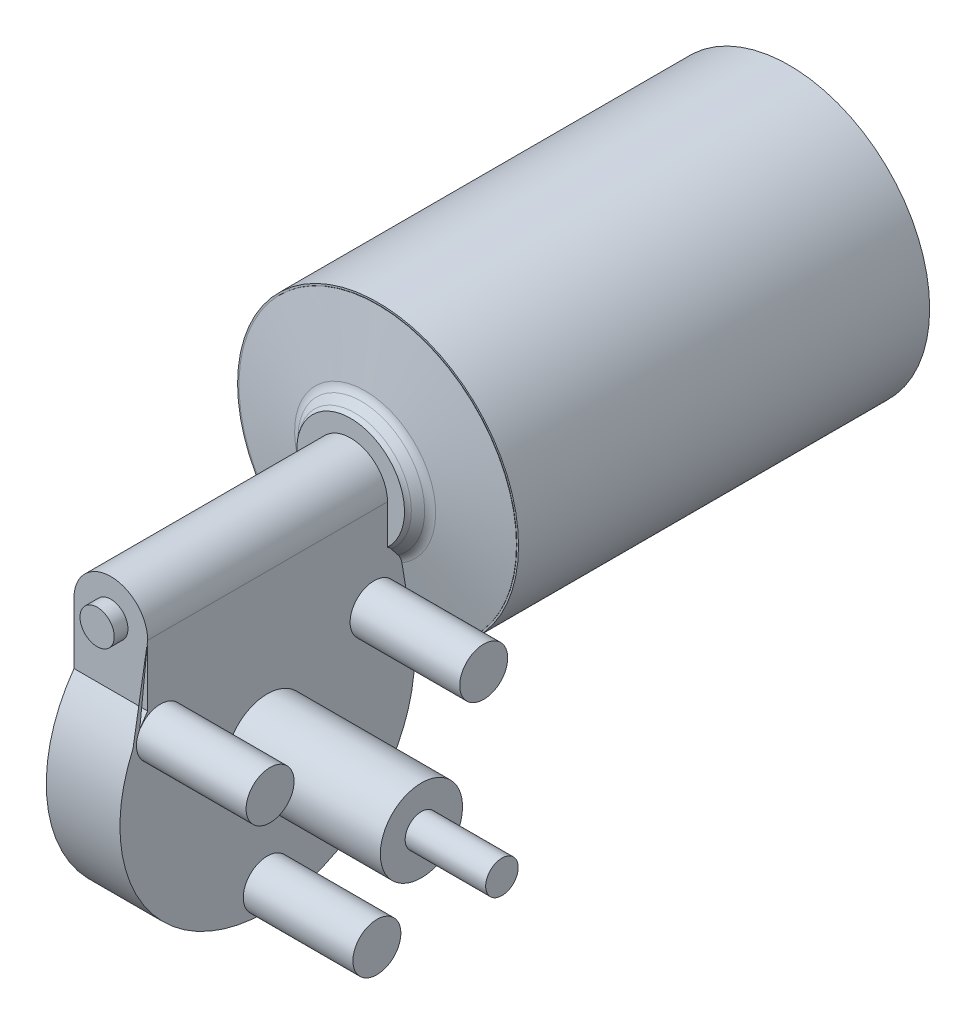
SolidWorks part; units mm, degrees
ref_plane "Front Plane" through (0, 0, 0) normal (0, 0, 1) x (1, 0, 0)
ref_plane "Top Plane" through (0, 0, 0) normal (0, 1, 0) x (1, 0, 0)
ref_plane "Right Plane" through (0, 0, 0) normal (1, 0, 0) x (0, 0, -1)
sketch "Sketch1" plane through (0, 0, 0) normal (0, 0, 1) x (1, 0, 0)
  circle A0 centre (0, 0) radius 41
  dimension "D1" = 82
extrude "Boss-Extrude1" add sketch "Sketch1" along normal mid plane 124
sketch "Sketch2" plane through (0, 0, 62) normal (0, 0, 1) x (1, 0, 0)
  circle A0 centre (0, 0) radius 41
extrude "Boss-Extrude2" add sketch "Sketch2" along normal mid plane 8
sketch "Sketch3" plane through (0, 0, 66) normal (0, 0, 1) x (1, 0, 0)
  circle A0 centre (0, 0) radius 40.5
  circle A1 centre (0, 0) radius 41 construction
  circle A2 centre (0, 0) radius 41
  dimension "D1" = 0.5
extrude "Cut-Extrude1" cut sketch "Sketch3" against normal blind 8
sketch "Sketch4" plane through (0, 0, 0) normal (1, 0, 0) x (0, 0, -1)
  line L0 (-58, 41) -> (-61.774, 20.5889)
  line L1 (-62.8789, 18.4878) -> (-64.8284, 16.5383)
  line L2 (-66, 40.5) -> (-66, -40.5) construction
  line L3 (-62, 19.1799) -> (-62, 50019.1799) construction
  line L4 (-58, 40.5) -> (-58, -40.5) construction
  line L5 (62, 41) -> (-58, 41) construction
  line L6 (0, 0) -> (50000, 0) construction
  line L7 (-58, 41) -> (-58, 44)
  line L8 (-58, 44) -> (-68, 44)
  line L9 (-68, 44) -> (-68, 15.3667)
  line L10 (-68, 15.3667) -> (-67.6569, 15.3667)
  arc A0 (-64.8284, 16.5383) -> (-67.6569, 15.3667) centre (-67.6569, 19.3667) cw
  arc A1 (-61.774, 20.5889) -> (-62.8789, 18.4878) centre (-65.7073, 21.3162) cw
  point P20 (-66, 15.3667)
  point P23 (-62, 19.3667)
  dimension "D6" = 4
  dimension "D1" = 22
  dimension "D2" = 45
  dimension "D3" = 4
  dimension "D4" = 3
  dimension "D5" = 10
revolve "Cut-Revolve1" cut sketch "Sketch4" angle 360 about L6
sketch "Sketch5" plane through (0, 0, 66) normal (0, 0, 1) x (1, 0, 0)
  circle A0 centre (0, 0) radius 10.75
  dimension "D1" = 21.5
extrude "Boss-Extrude3" add sketch "Sketch5" along normal blind 70 from surface at 0 starting at face at (-15.726, 0, 66)
sketch "Sketch6" plane through (0, 0, 136) normal (0, 0, 1) x (1, 0, 0)
  circle A0 centre (0, 0) radius 5
  dimension "D1" = 10
extrude "Boss-Extrude4" add sketch "Sketch6" along normal mid plane 8
sketch "Sketch7" plane through (0, 0, 0) normal (1, 0, 0) x (0, 0, -1)
  line L0 (0, 0) -> (50000, 0) construction
  line L1 (-58.0925, 0) -> (-58.0925, -50000) construction
  line L2 (-58.0925, 40.5) -> (-58.0925, -40.5) construction
  line L4 (-58.0925, -86) -> (49941.9075, -86) construction
  line L6 (-136, 0) -> (-136, -17.891)
  line L7 (-136, 10.75) -> (-136, -10.75) construction
  line L8 (-136, 0) -> (-58.0925, 0)
  line L9 (-58.0925, 0) -> (-58.0925, -43)
  arc A0 (-136, -17.891) -> (-58.0925, -43) centre (-101.0925, -43) ccw
  point P9 (-58.0925, 0)
  point P18 (0, 0)
  point P20 (0, 0)
  dimension "D1" = 86
extrude "Boss-Extrude5" add sketch "Sketch7" along normal mid plane 21.5
sketch "Sketch8" plane through (10.75, 0, 0) normal (1, 0, 0) x (0, 0, -1)
  line L0 (-101.0925, -43) -> (-101.0925, -50043) construction
  line L1 (-101.0925, -43) -> (-50101.0925, -43) construction
  line L2 (-101.0925, -43) -> (43200.1777, 24957) construction
  circle A0 centre (-101.0925, -43) radius 17 construction
  arc A1 (-136, -17.891) -> (-58.0925, -43) centre (-101.0925, -43) ccw construction
  circle A2 centre (-69.9155, -25) radius 7
  circle A3 centre (-101.0925, -79) radius 7
  circle A4 centre (-101.0925, -43) radius 17 construction
  circle A5 centre (-132.2694, -25) radius 7
  circle A6 centre (-101.0925, -43) radius 17 construction
  point P13 (0, 0)
  point P14 (0, 0)
  point P15 (-83.4901, -32.1865)
  point P22 (-101.0925, -43)
  dimension "D1" = 34
  dimension "D3" = 14
  dimension "D2" = 30
  dimension "D4" = 3
extrude "Boss-Extrude6" add sketch "Sketch8" along normal blind 32
sketch "Sketch9" plane through (10.75, 0, 0) normal (1, 0, 0) x (0, 0, -1)
  circle A0 centre (-101.0925, -43) radius 12
  arc A1 (-101.0925, -86) -> (-58.0925, -43) centre (-101.0925, -43) ccw construction
  dimension "D1" = 24
extrude "Boss-Extrude7" add sketch "Sketch9" along normal blind 45
sketch "Sketch10" plane through (55.75, 0, 0) normal (1, 0, 0) x (0, 0, -1)
  circle A0 centre (-101.0925, -43) radius 4.75
  dimension "D1" = 9.5
extrude "Boss-Extrude8" add sketch "Sketch10" along normal blind 23.5
